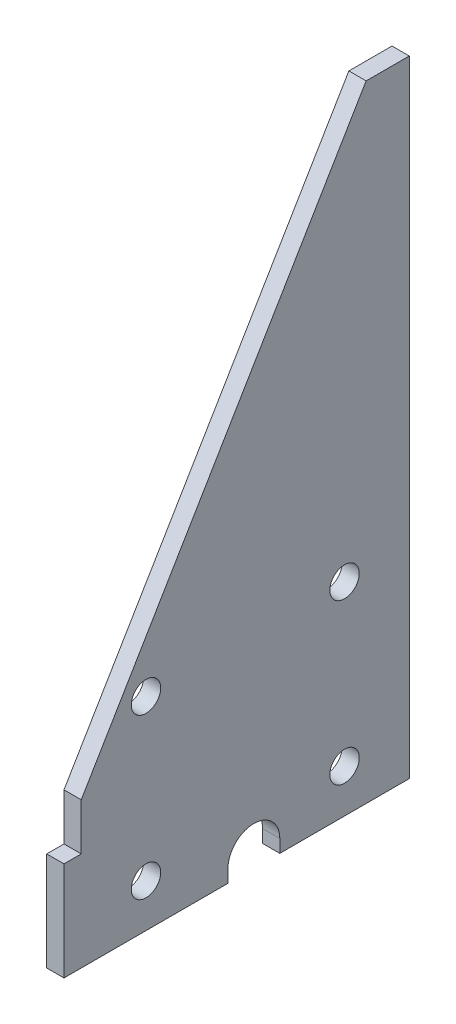
SolidWorks part; units mm, degrees
ref_plane "Front Plane" through (0, 0, 0) normal (0, 0, 1) x (1, 0, 0)
ref_plane "Top Plane" through (0, 0, 0) normal (0, 1, 0) x (1, 0, 0)
ref_plane "Right Plane" through (0, 0, 0) normal (1, 0, 0) x (0, 0, -1)
sketch "Sketch1" plane through (0, 0, 0) normal (1, 0, 0) x (0, 0, -1)
  line L0 (-38, -57.5) -> (42, -57.5)
  line L5 (32, 87.5) -> (-34, -23.7403)
  line L6 (-34, -23.7403) -> (-34, -34.6028)
  line L7 (-34, -34.6028) -> (-38, -34.6028)
  line L8 (-38, -34.6028) -> (-38, -57.5)
  line L9 (32, 87.5) -> (42, 87.5)
  line L11 (42, 87.5) -> (42, -57.5)
  line L12 (42, 187.5) -> (42, -57.5) construction
  line L13 (78, -57.5) -> (-38, -57.5) construction
  line L14 (-38, -34.6028) -> (-34, -34.6028) construction
  dimension "D1" = 10
extrude "Boss-Extrude1" add sketch "Sketch1" along normal blind 4 contours L5 L6 L7 L8 L0 L11 L9
sketch "Sketch2" plane through (0, 0, 0) normal (-1, 0, 0) x (0, 0, 1)
  line L0 (34, -34.6028) -> (34, -57.5)
  line L1 (38, -57.5) -> (-42, -57.5) construction
  line L2 (34, -57.5) -> (38, -57.5)
  line L3 (38, -57.5) -> (38, -34.6028)
  line L4 (38, -34.6028) -> (34, -34.6028)
sketch "Sketch3" plane through (0, 0, 0) normal (-1, 0, 0) x (0, 0, 1)
  line L0 (34, -23.7403) -> (34, -34.6028) construction
  line L1 (38, -57.5) -> (-42, -57.5) construction
  circle A0 centre (-27, -10.5) radius 3.41
  circle A1 centre (19, -10.5) radius 3.41
  dimension "D1" = 6.82
  dimension "D2" = 15
  dimension "D3" = 47
  dimension "D4" = 46
extrude "Cut-Extrude1" cut sketch "Sketch3" against normal up to next
sketch "Sketch4" plane through (0, 0, 0) normal (-1, 0, 0) x (0, 0, 1)
  line L0 (38, -34.6028) -> (38, -57.5) construction
  line L1 (38, -57.5) -> (-42, -57.5) construction
  circle A0 centre (-27, -47.5) radius 3.41
  circle A1 centre (19, -47.5) radius 3.41
  dimension "D1" = 6.82
  dimension "D2" = 19
  dimension "D3" = 46
  dimension "D4" = 10
extrude "Cut-Extrude2" cut sketch "Sketch4" against normal up to next
sketch "Sketch5" plane through (4, 0, 0) normal (1, 0, 0) x (0, 0, -1)
  circle A0 centre (37, 73.324) radius 2.5
  circle A1 centre (37, 73.324) radius 2.5 construction
sketch "Sketch6" plane through (4, 0, 0) normal (1, 0, 0) x (0, 0, -1)
  line L0 (0, -54.5) -> (0, -57.5)
  line L1 (-38, -57.5) -> (42, -57.5) construction
  line L2 (0, -57.5) -> (12, -57.5)
  line L3 (12, -57.5) -> (12, -54.5)
  arc A0 (12, -54.5) -> (0, -54.5) centre (6, -54.5) ccw
  dimension "D1" = 6
  dimension "D2" = 3
  dimension "D3" = 30
extrude "Cut-Extrude4" cut sketch "Sketch6" against normal up to next
equation "\"Printed Hole Size\"= 6.5"
equation "\"CAD Hole Size\"= 0.9683 * \"Printed Hole Size\" + 0.5265"
